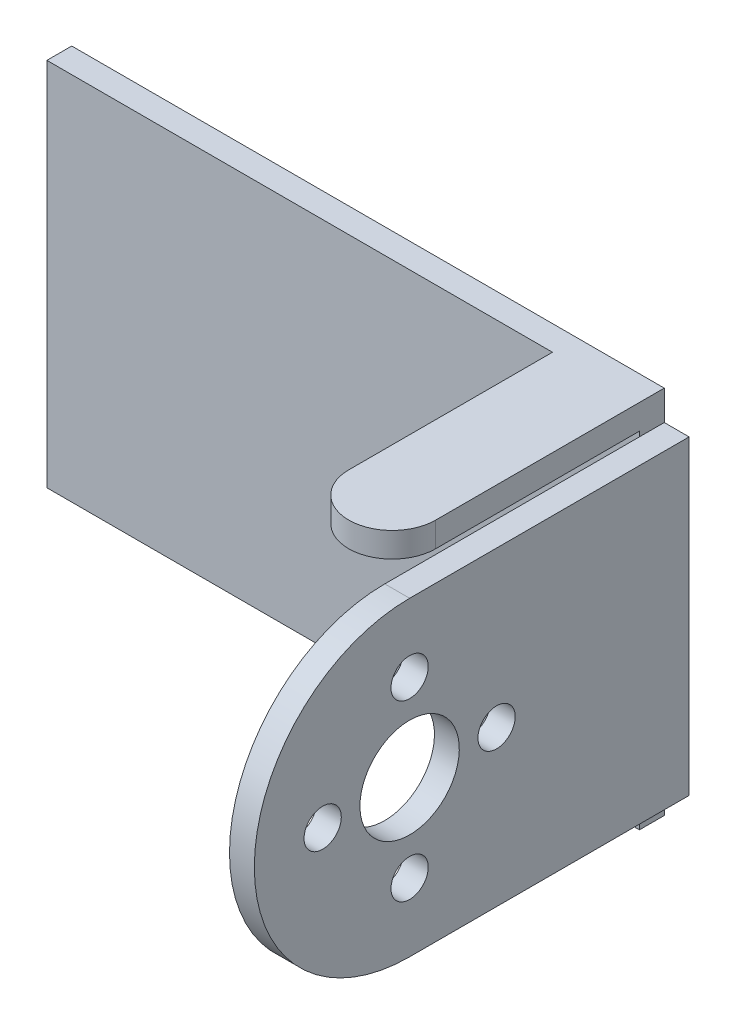
SolidWorks part; units mm, degrees
ref_plane "정면" through (0, 0, 0) normal (0, 0, 1) x (1, 0, 0)
ref_plane "윗면" through (0, 0, 0) normal (0, 1, 0) x (1, 0, 0)
ref_plane "우측면" through (0, 0, 0) normal (1, 0, 0) x (0, 0, -1)
sketch "스케치1" plane through (0, 0, 0) normal (0, 0, 1) x (1, 0, 0)
  line L1 (-23.85, 14.9) -> (23.85, 14.9)
  line L2 (-23.85, 14.9) -> (-23.85, -14.9)
  line L3 (-23.85, -14.9) -> (23.85, -14.9)
  line L4 (23.85, 14.9) -> (23.85, -14.9)
  line L5 (-23.85, 14.9) -> (23.85, -14.9) construction
  line L6 (-23.85, -14.9) -> (23.85, 14.9) construction
  point P0 (0, 0)
  dimension "D1" = 47.7
  dimension "D2" = 29.8
extrude "보스-돌출1" add sketch "스케치1" along normal blind 2
sketch "스케치2" plane through (0, 0, 2) normal (0, 0, 1) x (1, 0, 0)
  line L7 (23.85, 14.9) -> (23.85, 12.9)
  line L8 (16.85, 12.9) -> (23.85, 12.9)
  line L9 (16.85, 14.9) -> (16.85, 12.9)
  line L10 (23.85, 14.9) -> (16.85, 14.9)
extrude "보스-돌출3" add sketch "스케치2" along normal blind 19.9
sketch "스케치3" plane through (0, 12.9, 0) normal (0, -1, 0) x (1, 0, 0)
  line L5 (16.85, 2) -> (23.85, 2)
  line L6 (23.85, 2) -> (23.85, 21.9)
  line L7 (23.85, 21.9) -> (16.85, 21.9)
  line L8 (16.85, 21.9) -> (16.85, 2)
  line L10 (23.85, 18.4) -> (23.85, 21.9)
  line L11 (23.85, 21.9) -> (16.85, 21.9)
  line L12 (16.85, 21.9) -> (16.85, 18.4)
  arc A0 (23.85, 18.4) -> (16.85, 18.4) centre (20.35, 18.4) ccw
  line M8 (23.85, 2) -> (23.85, 21.9)
  line M9 (23.85, 21.9) -> (16.85, 21.9)
  line M10 (16.85, 21.9) -> (16.85, 2)
  dimension "D1" = 0
extrude "컷-돌출1" cut sketch "스케치3" against normal through all contours A0 L11 M10 | A0 M8 M9
ref_plane "평면1" through (23.85, 0, 0) normal (1, 0, 0) x (0, 0, -1)
sketch "스케치4" plane through (23.85, 0, 0) normal (1, 0, 0) x (0, 0, -1)
  line L0 (0, 12.5) -> (0, -12.5)
  line L1 (0, -14.9) -> (0, 14.9) construction
  line L3 (0, 12.5) -> (-22.5, 12.5)
  line L4 (0, -12.5) -> (-22.5, -12.5)
  arc A0 (-22.5, 12.5) -> (-22.5, -12.5) centre (-22.5, 0) ccw
  circle A1 centre (-22.5, 0) radius 4
  circle A3 centre (-29.5, 0) radius 1.5
  circle A4 centre (-22.5, 7) radius 1.5
  circle A5 centre (-15.5, 0) radius 1.5
  circle A6 centre (-22.5, -7) radius 1.5
  point P4 (0, 0)
  point P24 (-22.5, 0)
  dimension "D1" = 4
extrude "보스-돌출4" add sketch "스케치4" along normal blind 2
sketch "스케치5" plane through (23.85, 0, 0) normal (1, 0, 0) x (0, 0, -1)
  line L0 (0, 12.5) -> (0, -12.5)
  line L1 (0, -14.9) -> (0, -12.5) construction
  line L5 (-22.5, -12.5) -> (0, -12.5)
  line L6 (0, 12.5) -> (-22.5, 12.5)
  circle A0 centre (-22.5, 0) radius 4
  circle A1 centre (-15.5, 0) radius 1.5
  circle A2 centre (-22.5, -7) radius 1.5
  circle A3 centre (-22.5, 0) radius 4
  circle A4 centre (-29.5, 0) radius 1.5
  circle A5 centre (-22.5, 0) radius 4
  circle A6 centre (-22.5, 7) radius 1.5
  circle A7 centre (-22.5, 0) radius 4
  arc A8 (-22.5, 12.5) -> (-22.5, -12.5) centre (-22.5, 0) ccw
  point P4 (0, 0)
  point P23 (-22.5, 0)
  dimension "D1" = 7
  dimension "D2" = 3
extrude "보스-돌출5" add sketch "스케치5" along normal blind 2 contours L6 A8 L5 L0 A0 A1 A2 A4 A6
